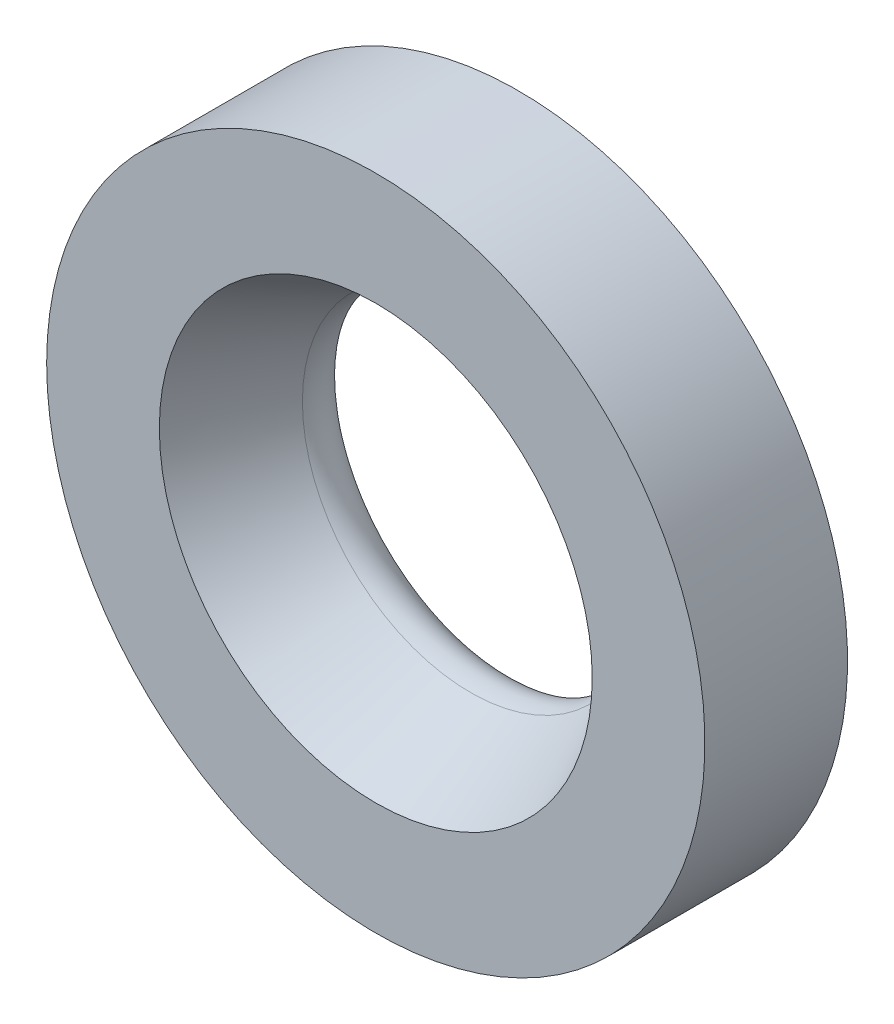
SolidWorks part; units mm, degrees
ref_plane "Front Plane" through (0, 0, 0) normal (1, 0, 0) x (0, 1, 0)
ref_plane "Top Plane" through (0, 0, 0) normal (0, 0, 1) x (0, 1, 0)
ref_plane "Right Plane" through (0, 0, 0) normal (0, 1, 0) x (-1, 0, 0)
sketch "Sketch2" plane through (0, 0, 0) normal (1, 0, 0) x (0, 1, 0)
  line L0 (1000, 0) -> (0, 0) construction
  line L1 (0, 0) -> (0, 13318.7485) construction
  line L2 (-15, 0) -> (-9.8641, 0)
  line L3 (-15, 0) -> (-15, -6.5)
  line L4 (-15, -6.5) -> (-13.5, -6.5)
  line L5 (-13.5, -6.5) -> (-13.5, -1.5)
  line L6 (-13.5, -1.5) -> (-10.7833, -1.5)
  line L7 (-10.7833, -1.5) -> (-9.681, -3.6635)
  line L8 (-7.6635, -4.319) -> (-9.8641, 0)
  line L9 (-9.8641, 0) -> (-13318.7485, 0) construction
  arc A0 (-9.681, -3.6635) -> (-7.6635, -4.319) centre (-9, -5) ccw
  dimension "D1" = 3
  dimension "D8" = 63
  dimension "D2" = 1.5
  dimension "D3" = 9
  dimension "D4" = 15
  dimension "D5" = 1.5
  dimension "D6" = 1.5
  dimension "D7" = 6.5
  dimension "D9" = 1.5
revolve "Revolve1" add sketch "Sketch2" angle 360 about L1
